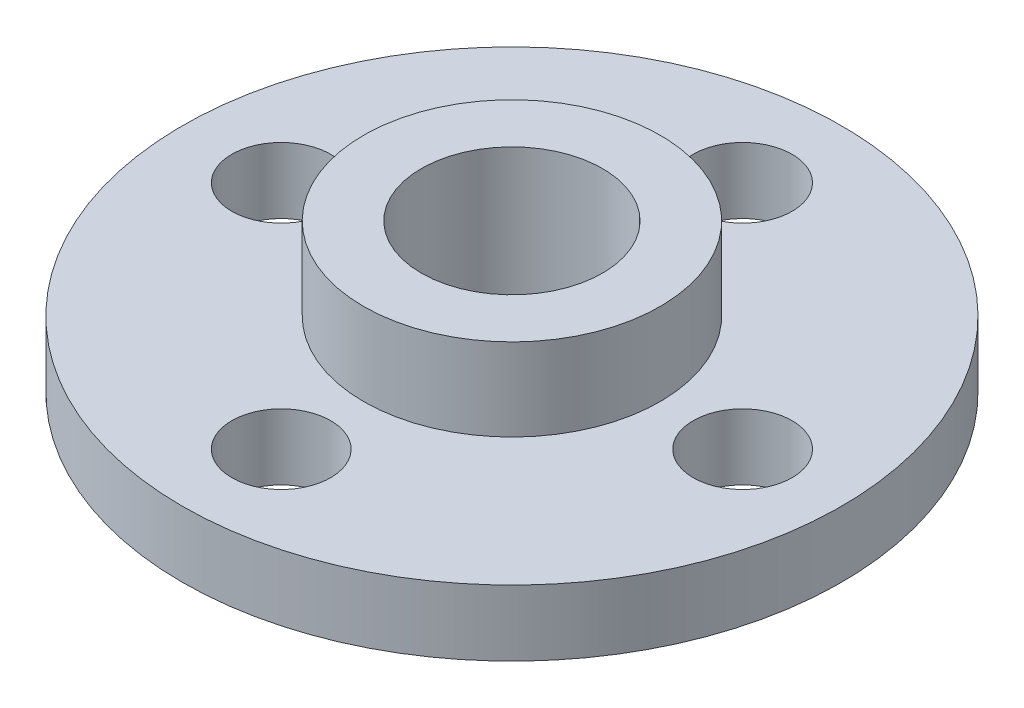
SolidWorks part; units mm, degrees
ref_plane "Front Plane" through (0, 0, 0) normal (0, 0, 1) x (1, 0, 0)
ref_plane "Top Plane" through (0, 0, 0) normal (0, 1, 0) x (1, 0, 0)
ref_plane "Right Plane" through (0, 0, 0) normal (1, 0, 0) x (0, 0, -1)
sketch "草图1" plane through (0, 0, 0) normal (0, 1, 0) x (1, 0, 0)
  circle A0 centre (0, 0) radius 10
  circle A1 centre (7, 0) radius 1.5
  circle A2 centre (0, 0) radius 10
  circle A3 centre (0, -7) radius 1.5
  circle A4 centre (0, 0) radius 10
  circle A5 centre (-7, 0) radius 1.5
  circle A6 centre (0, 0) radius 10
  circle A7 centre (0, 7) radius 1.5
  point P17 (0, 0)
  dimension "D1" = 20
  dimension "D2" = 3
  dimension "D4" = 7
  dimension "D3" = 4
extrude "凸台-拉伸1" add sketch "草图1" along normal blind 2 contours A0 A7 A5 A3 A1
sketch "草图2" plane through (0, 2, 0) normal (0, 1, 0) x (1, 0, 0)
  circle A0 centre (0, 0) radius 4.5
  circle A1 centre (0, 0) radius 2.75
  dimension "D1" = 9
  dimension "D2" = 5.5
extrude "凸台-拉伸2" add sketch "草图2" along normal blind 2.5
sketch "草图3" plane through (0, 2, 0) normal (0, 1, 0) x (1, 0, 0)
  circle A1 centre (0, 0) radius 2.75
  circle A2 centre (0, 0) radius 2.75
  dimension "D1" = 0
extrude "切除-拉伸1" cut sketch "草图3" against normal through all
